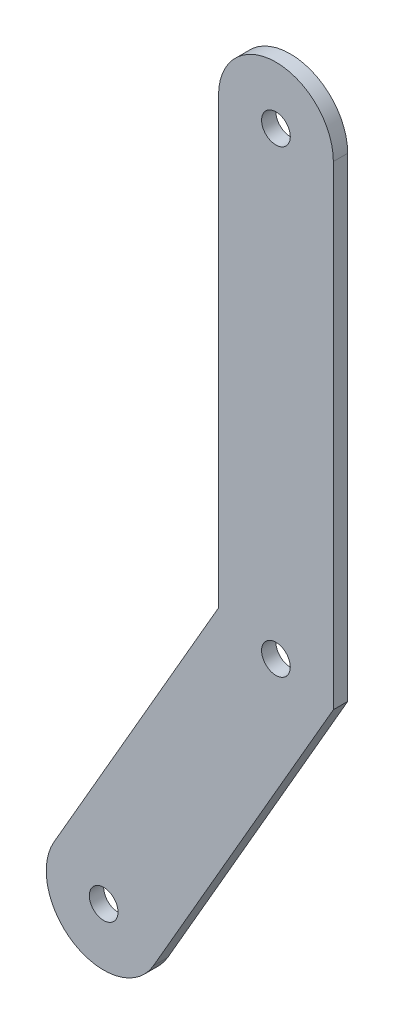
SolidWorks part; units mm, degrees
material "5052-H32"
ref_plane "Front Plane" through (0, 0, 0) normal (0, 0, 1) x (1, 0, 0)
ref_plane "Top Plane" through (0, 0, 0) normal (0, 1, 0) x (1, 0, 0)
ref_plane "Right Plane" through (0, 0, 0) normal (1, 0, 0) x (0, 0, -1)
sketch "Sketch1" plane through (0, 0, 0) normal (0, 0, 1) x (1, 0, 0)
  line L2 (-108.4059, -695.7645) -> (50.8, -420.0118)
  line L5 (50.8, -420.0118) -> (50.8, 0)
  line L6 (-50.8, 0) -> (-50.8, -392.7882)
  line L7 (-50.8, -392.7882) -> (-196.3941, -644.9645)
  line L8 (-152.4, -670.3645) -> (0, -406.4) construction
  line L9 (0, -406.4) -> (0, 0) construction
  line L10 (-50.8, -392.7882) -> (0, -406.4) construction
  line L11 (0, -406.4) -> (50.8, -420.0118) construction
  line L12 (-108.4059, -695.7645) -> (-268.2355, -1010.3745) construction
  line L14 (-358.7518, -964.39) -> (-197.6906, -647.3558) construction
  arc A6 (50.8, 0) -> (-50.8, 0) centre (0, 0) ccw
  arc A7 (-196.3941, -644.9645) -> (-108.4059, -695.7645) centre (-152.4, -670.3645) ccw
  circle A8 centre (0, 0) radius 12.7
  circle A9 centre (-152.4, -670.3645) radius 12.7
  circle A10 centre (0, -406.4) radius 12.7
  arc A11 (-358.7518, -964.39) -> (-268.2355, -1010.3745) centre (-313.4936, -987.3822) ccw construction
  arc A12 (-197.6906, -647.3558) -> (-196.3941, -644.9645) centre (-152.4, -670.3645) cw construction
  dimension "D1" = 101.6
  dimension "D3" = 150
  dimension "D4" = 304.8
  dimension "D5" = 304.8
  dimension "D2" = 25.4
  dimension "D6" = 406.4
  dimension "D7" = 355.6
  dimension "D8" = 176.932
extrude "Boss-Extrude1" add sketch "Sketch1" along normal blind 12.7
